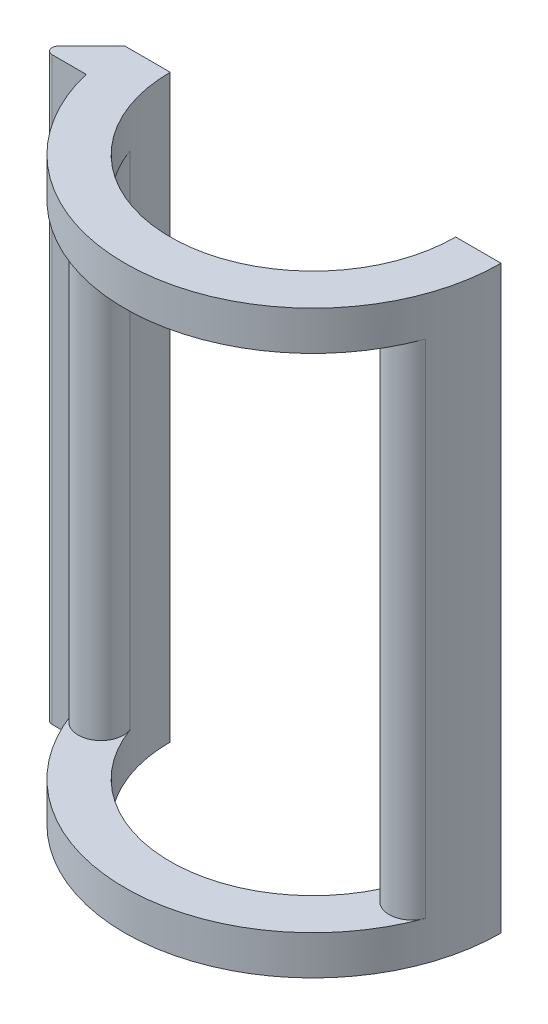
SolidWorks part; units mm, degrees
ref_plane "Front Plane" through (0, 0, 0) normal (0, 0, 1) x (1, 0, 0)
ref_plane "Top Plane" through (0, 0, 0) normal (0, 1, 0) x (1, 0, 0)
ref_plane "Right Plane" through (0, 0, 0) normal (1, 0, 0) x (0, 0, -1)
sketch "Sketch4" plane through (0, 0, 0) normal (0, 1, 0) x (1, 0, 0)
  line L0 (-28.9052, 0) -> (-38.1, 0)
  line L2 (-38.1, -8.89) -> (-46.99, -8.89)
  line L3 (-46.99, -8.89) -> (-38.1, 0)
  line L4 (28.9052, 0) -> (38.1, 0)
  line L5 (-38.1, -8.89) -> (-37.0483, -8.89)
  arc A0 (-28.9052, 0) -> (28.9052, 0) centre (0, 0) ccw
  arc A1 (38.1, 0) -> (-37.0483, -8.89) centre (0, 0) cw
  dimension "D1" = 57.8104
  dimension "D2" = 76.2
  dimension "D3" = 8.89
  dimension "D4" = 8.89
extrude "Boss-Extrude1" add sketch "Sketch4" along normal blind 117.475
fillet "Fillet2" radius 1.27 1 edges at (-46.99, 58.7375, 8.89)
sketch "Sketch5" plane through (0, 0, 0) normal (0, 0, 1) x (1, 0, 0)
  line L0 (-37.0483, 117.475) -> (-37.0483, 0) construction
  line L1 (-24.3483, 6.35) -> (25.4, 6.35)
  line L2 (-24.3483, 6.35) -> (-24.3483, 111.125)
  line L3 (-24.3483, 111.125) -> (25.4, 111.125)
  line L4 (25.4, 6.35) -> (25.4, 111.125)
  line L5 (38.1, 117.475) -> (-37.0483, 117.475) construction
  line L6 (38.1, 117.475) -> (38.1, 0) construction
  line L7 (20.955, 0) -> (-20.955, 0) construction
  dimension "D1" = 12.7
  dimension "D2" = 6.35
  dimension "D3" = 12.7
  dimension "D4" = 6.35
sketch "Sketch6" plane through (0, 0, 0) normal (0, 1, 0) x (1, 0, 0)
  line L0 (0, 0) -> (-48.3523, -17.5988) construction
  line L1 (0, 0) -> (55.3566, -20.1481) construction
  line L2 (0, -20.955) -> (0, 20.955) construction
  circle A0 centre (0, 0) radius 38.1 construction
  arc A1 (-35.8023, -13.031) -> (35.8023, -13.031) centre (0, 0) ccw
  arc A2 (27.162, -9.8862) -> (-27.162, -9.8862) centre (0, 0) cw
  arc A3 (-28.9052, 0) -> (28.9052, 0) centre (0, 0) ccw construction
  arc A4 (-35.8023, -13.031) -> (-27.162, -9.8862) centre (-31.4821, -11.4586) ccw
  arc A5 (35.8023, -13.031) -> (27.162, -9.8862) centre (31.4821, -11.4586) cw
  dimension "D1" = 70
  dimension "D2" = 70
extrude "Cut-Extrude2" cut sketch "Sketch6" along normal blind 101.6 from offset 7.9375
